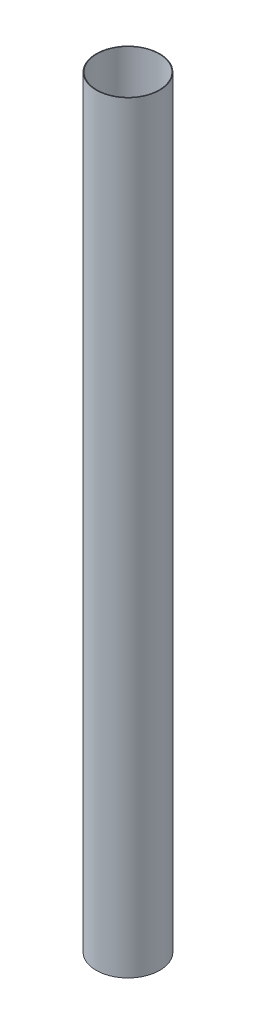
SolidWorks part; units mm, degrees
other "标注1"
sketch "草图2" plane through (50, 0, -50) normal (1, 0, 0) x (0, 0, -1)
other "细节项目1"
material "玻璃"
ref_plane "前视基准面" through (0, 0, 0) normal (0, 0, 1) x (1, 0, 0)
ref_plane "上视基准面" through (0, 0, 0) normal (0, 1, 0) x (1, 0, 0)
ref_plane "右视基准面" through (0, 0, 0) normal (1, 0, 0) x (0, 0, -1)
sketch "草图1" plane through (0, 0, 0) normal (0, 1, 0) x (1, 0, 0)
  circle A0 centre (0, 0) radius 50
  circle A1 centre (0, 0) radius 49
  dimension "D1" = 100
  dimension "D2" = 98
extrude "凸台-拉伸1" add sketch "草图1" along normal blind 1200
